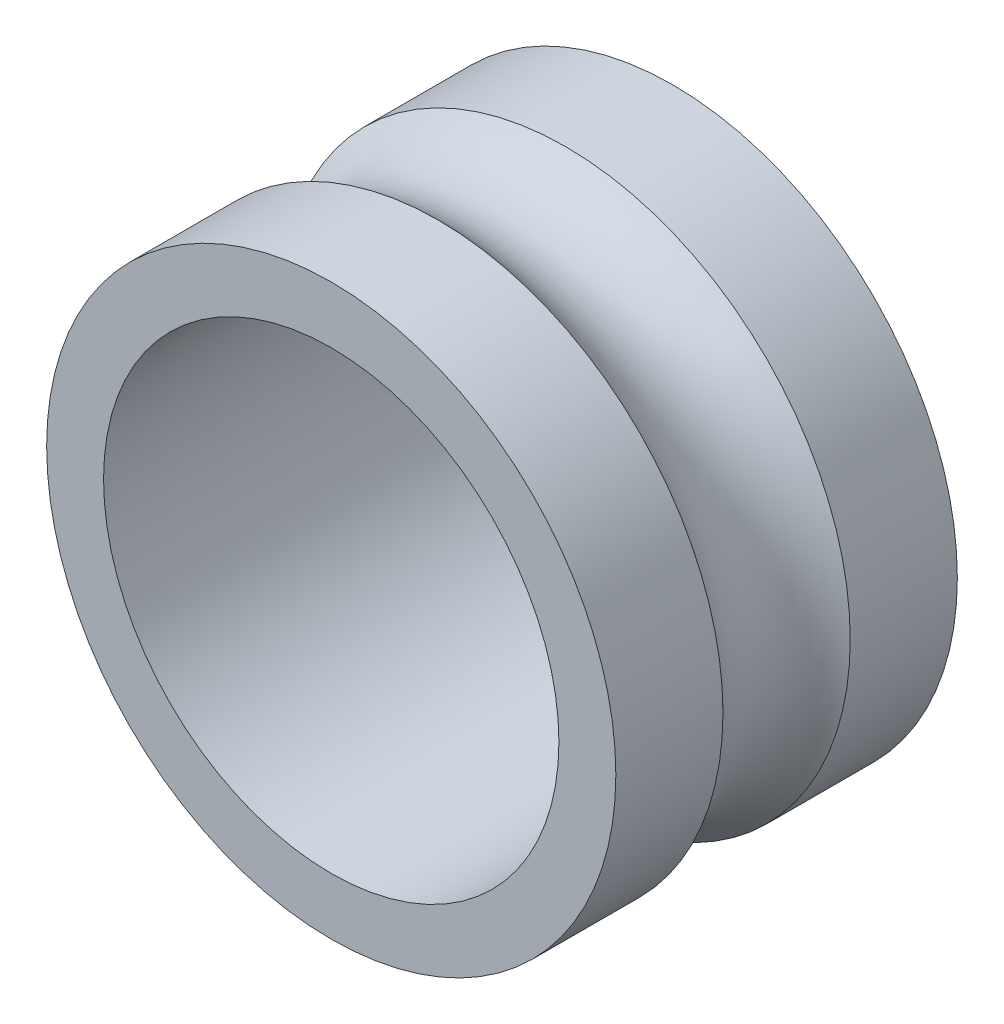
SolidWorks part; units mm, degrees
material "AISI 4340 Acier normalisé"
ref_plane "Face" through (0, 0, 0) normal (0, 0, 1) x (1, 0, 0)
ref_plane "Dessus" through (0, 0, 0) normal (0, 1, 0) x (1, 0, 0)
ref_plane "Droite" through (0, 0, 0) normal (1, 0, 0) x (0, 0, -1)
sketch "Esquisse1" plane through (0, 0, 0) normal (0, 0, 1) x (1, 0, 0)
  circle A0 centre (0, 0) radius 2
  circle A1 centre (0, 0) radius 2.5
  dimension "D1" = 4
  dimension "D2" = 5
extrude "Boss.-Extru.1" add sketch "Esquisse1" along normal mid plane 3
sketch "Esquisse2" plane through (0, 0, 0) normal (0, 1, 0) x (1, 0, 0)
  line L0 (0, 1.5) -> (0, -1.5) construction
  line L1 (-2.5, -1.5) -> (2.5, -1.5) construction
  line L2 (2.5, -1.5) -> (2.5, 1.5) construction
  line L3 (2.5, -0.559) -> (2.5, 0.559)
  line L4 (0, 0) -> (2.5, 0) construction
  line L5 (2.5, 1.5) -> (-2.5, 1.5) construction
  arc A0 (2.5, 0.559) -> (2.5, -0.559) centre (3, 0) ccw
  dimension "D1" = 0.75
  dimension "D2" = 0.5
revolve "Enlèvement de matière-Révolution1" cut sketch "Esquisse2" angle 360 about L0
